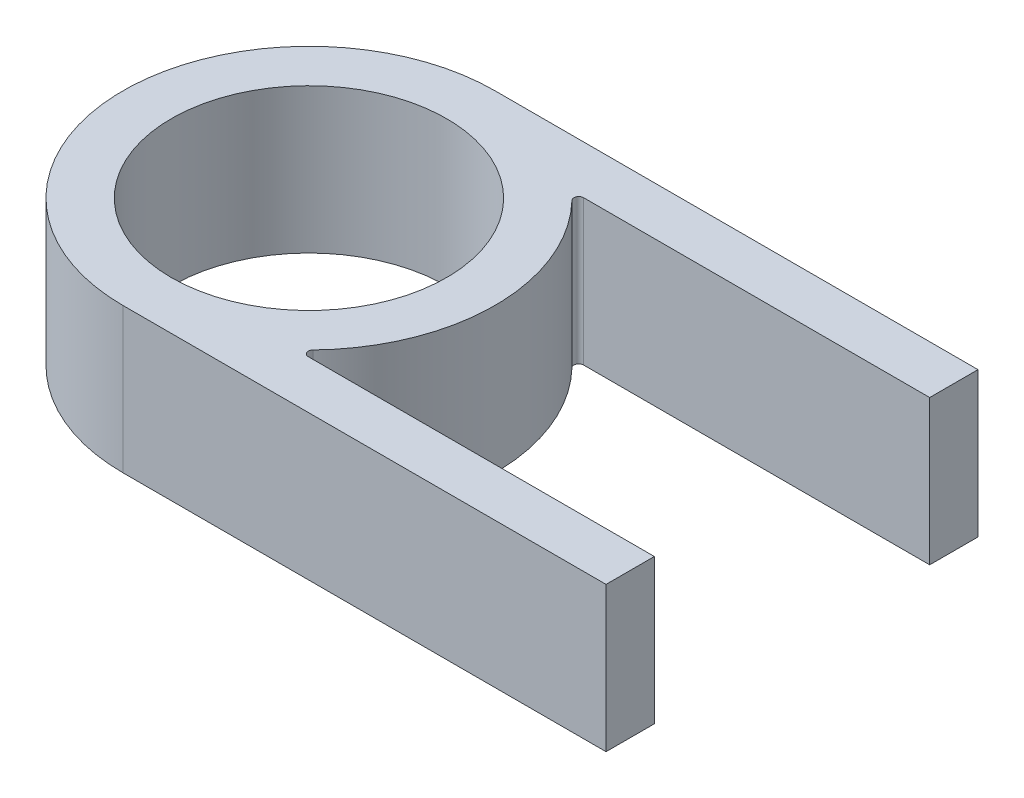
SolidWorks part; units mm, degrees
ref_plane "前视基准面" through (0, 0, 0) normal (0, 0, 1) x (1, 0, 0)
ref_plane "上视基准面" through (0, 0, 0) normal (0, 1, 0) x (1, 0, 0)
ref_plane "右视基准面" through (0, 0, 0) normal (1, 0, 0) x (0, 0, -1)
sketch "草图1" plane through (0, 0, 0) normal (0, 1, 0) x (1, 0, 0)
  line L0 (28.3549, -28.5) -> (100, -28.5)
  line L1 (-46.3283, 0) -> (52.0613, 0) construction
  line L2 (0, 30.0611) -> (0, -44.0924) construction
  line L3 (0, -38.5) -> (100, -38.5)
  line L4 (100, -38.5) -> (100, -28.5)
  line L5 (0, 38.5) -> (100, 38.5)
  line L6 (28.3549, 28.5) -> (100, 28.5)
  line L7 (100, 38.5) -> (100, 28.5)
  circle A0 centre (0, 0) radius 28.5
  arc A1 (27.637, -26.8038) -> (27.637, 26.8038) centre (0, 0) ccw
  arc A2 (0, 38.5) -> (0, -38.5) centre (0, 0) ccw
  arc A3 (28.3549, 28.5) -> (27.637, 26.8038) centre (28.3549, 27.5) ccw
  arc A4 (27.637, -26.8038) -> (28.3549, -28.5) centre (28.3549, -27.5) ccw
  dimension "D1" = 57
  dimension "D2" = 10
  dimension "D4" = 1
  dimension "D3" = 100
extrude "凸台-拉伸1" add sketch "草图1" along normal blind 30
